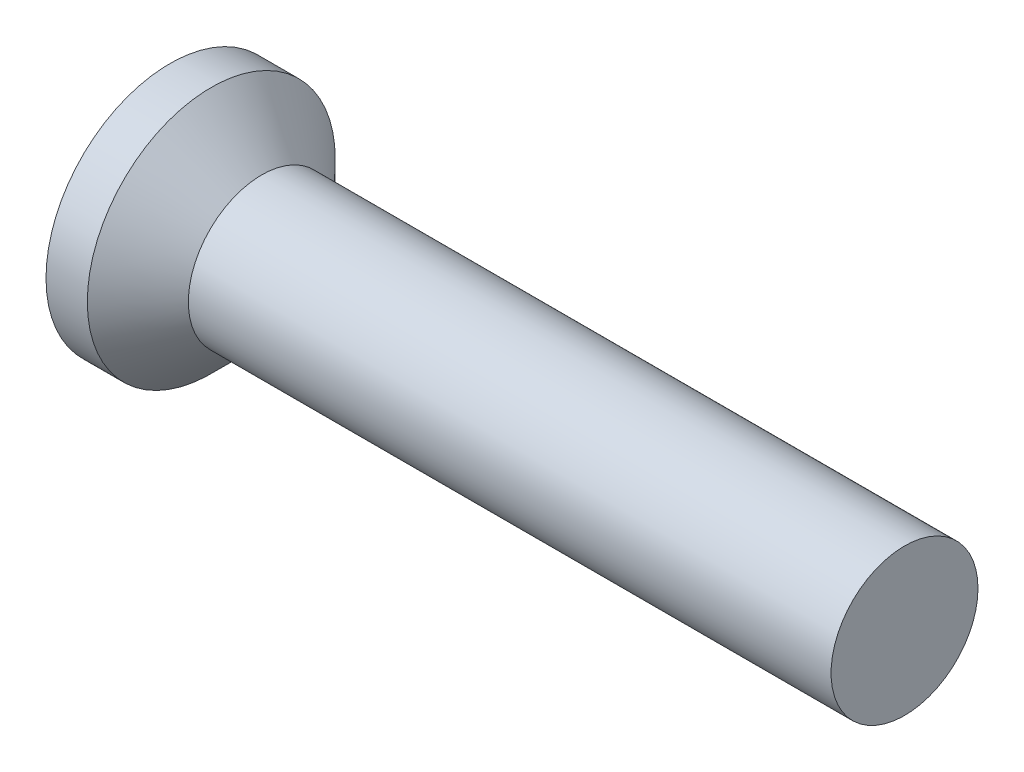
SolidWorks part; units mm, degrees
ref_plane "Front" through (0, 0, 0) normal (0, 0, 1) x (1, 0, 0)
ref_plane "Top" through (0, 0, 0) normal (0, 1, 0) x (1, 0, 0)
ref_plane "Right" through (0, 0, 0) normal (1, 0, 0) x (0, 0, -1)
sketch "Sketch1" plane through (0, 0, 0) normal (0, 0, 1) x (1, 0, 0)
  line L0 (8, 0.8) -> (1.7, 0.8)
  line L1 (1.7, 0.8) -> (1, 0.8)
  line L2 (1, 0.8) -> (0.45, 1.35)
  line L3 (0.45, 1.35) -> (0, 1.35)
  line L4 (8, 0.8) -> (8, 0)
  line L5 (4.5158, 0) -> (-89.8219, 0) construction
  line L6 (8, 0) -> (0, 0)
  line L7 (0, 1.35) -> (0, 0)
  dimension "D1" = 45
  dimension "dk" = 2.7
  dimension "l" = 8
  dimension "k" = 1
  dimension "a" = 0.7
  dimension "d" = 1.6
revolve "Base" add sketch "Sketch1" angle 360 about L5
cosmetic thread "ThreadCosmetic1" [suppressed] parameters "bb"=7
sketch "Sketch6" plane through (0, 0, 0) normal (1, 0, 0) x (0, 0, -1)
  line L0 (-1.9271, 0) -> (2.0512, 0) construction
  line L1 (0, 1.8651) -> (0, -2.0207) construction
  line L2 (0.16, 0.16) -> (0.16, 0.8)
  line L3 (0.16, 0.8) -> (-0.16, 0.8)
  line L4 (-0.16, 0.16) -> (-0.16, 0.8)
  line L5 (0.16, 0.16) -> (0.8, 0.16)
  line L6 (0.8, 0.16) -> (0.8, -0.16)
  line L7 (-0.8, 0.16) -> (-0.8, -0.16)
  line L8 (-0.16, 0.16) -> (-0.8, 0.16)
  line L9 (-0.16, -0.16) -> (-0.8, -0.16)
  line L10 (0.16, -0.16) -> (0.8, -0.16)
  line L11 (-0.16, -0.16) -> (-0.16, -0.8)
  line L12 (0.16, -0.8) -> (-0.16, -0.8)
  line L13 (0.16, -0.16) -> (0.16, -0.8)
  point P16 (-0.8, 0)
  point P17 (0.8, 0)
extrude "CrossRecess" cut sketch "Sketch6" along normal blind 0.5
draft "Draft9" type of draft neutral plane draft angle 30 faces to draft 4 face at (0.25, 0.8, 0) face at (0.25, 0, 0.8) face at (0.25, -0.8, 0) face at (0.25, 0, -0.8) neutral plane through (0, 1.35, 0) neutral plane normal (-1, 0, 0) parameters "D1"=30
fillet "Fillet5" radius 0.3 4 edges at (0.25, -0.16, -0.16) (0.25, 0.16, -0.16) (0.25, 0.16, 0.16) (0.25, -0.16, 0.16)
sketch "Sketch7" plane through (0, 0, 0) normal (1, 0, 0) x (0, 0, -1)
  line L0 (-2.0126, 0) -> (1.9757, 0) construction
  line L1 (0, 1.9314) -> (0, -2.0126) construction
  line L2 (0, 0) -> (1.5555, 1.5555) construction
  line L3 (0, 0.2391) -> (0.5657, 0.5657)
  line L4 (-1.5402, 1.5402) -> (0, 0) construction
  line L5 (0.2391, 0) -> (0.5657, 0.5657)
  line L6 (0, -0.2391) -> (0.5657, -0.5657)
  line L7 (0.2391, 0) -> (0.5657, -0.5657)
  line L8 (-0.2391, 0) -> (-0.5657, -0.5657)
  line L9 (0, -0.2391) -> (-0.5657, -0.5657)
  line L10 (-0.2391, 0) -> (-0.5657, 0.5657)
  line L11 (0, 0.2391) -> (-0.5657, 0.5657)
  dimension "D3" = 15
  dimension "m" = 1.6
extrude "Cut-Extrude3" [suppressed] cut sketch "Sketch7" along normal blind 10 draft 20
sketch "Sketch8" plane through (0, 0, 0) normal (0, 0, 1) x (1, 0, 0)
  line L0 (-17, 0.9895) -> (-17.9, 0.8)
  line L1 (-17.9, 0.8) -> (1, 0.8)
  line L3 (8, -0.8) -> (8, 0.8) construction
  line L6 (1, 0.8) -> (1, 5.8)
  line L7 (1, 5.8) -> (-17, 5.8)
  line L8 (-17, 5.8) -> (-17, 0.9895)
  line L9 (62.4753, 0.1895) -> (52.9594, 0.1895) construction
  dimension "D1" = 5
  dimension "x" = 0.9
  dimension "d" = 1.6
  dimension "THD_MINOR" = 1.221
  dimension "b" = 25
sketch "Sketch9" plane through (0, 0, 0) normal (0, 0, 1) x (1, 0, 0)
  line L0 (8, 0.6359) -> (8.0947, 0.8)
  line L1 (8.0947, 0.8) -> (8.0947, 0.9895)
  line L2 (8.0947, 0.9895) -> (7.9052, 0.9895)
  line L3 (7.9052, 0.9895) -> (7.9052, 0.8)
  line L4 (7.9052, 0.8) -> (8, 0.6359)
  line L5 (0, 0) -> (73.843, 0) construction
  line L6 (8, -0.8) -> (8, 0.8) construction
  dimension "D1" = 1.6
  dimension "D2" = 0.1895
revolve "Cut-Revolve10" [suppressed] cut sketch "Sketch9" angle 360 about L5
pattern_linear "LPattern10" [suppressed] count 31 spacing 0.2274 along (1, 0, 0)
equation "\"D1@Sketch6\" = \"m@Sketch6\" / 5"
equation "\"D1@CrossRecess\" = \"k@Sketch1\" / 2"
equation "\"D1@Sketch9\" = \"d@Sketch1\""
equation "\"D2@Sketch9\" =  ( \"d@Sketch1\" - \"THD_MINOR@ThreadCosmetic1\" )  / 2"
equation "\"D3@LPattern10\" = \"D2@Sketch9\" * 1.2"
equation "\"D1@LPattern10\" = \"bb@ThreadCosmetic1\" / \"D3@LPattern10\" "
